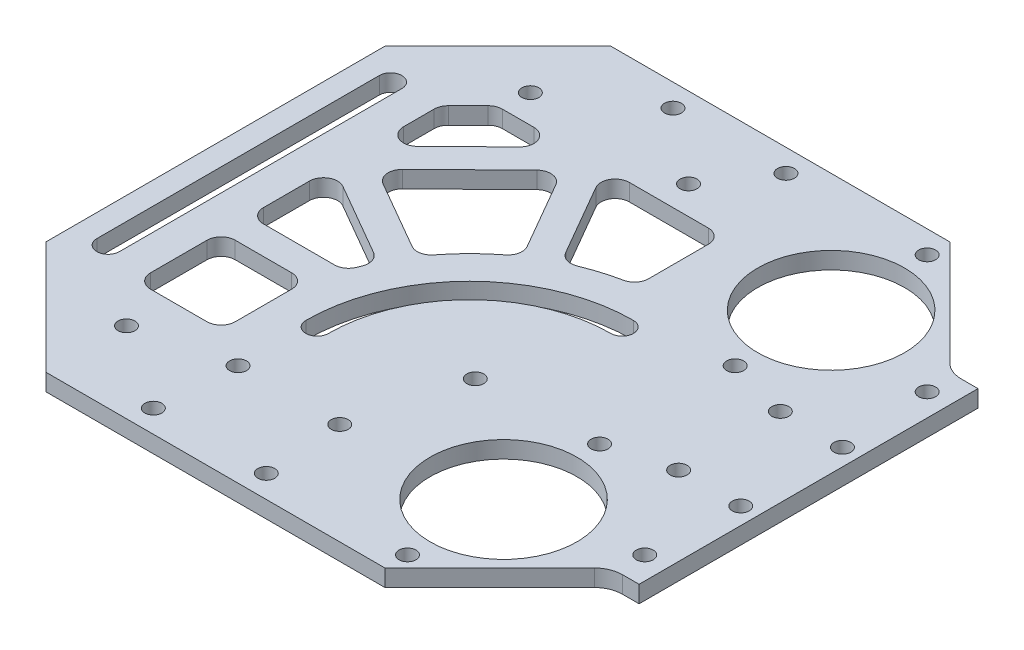
SolidWorks part; units mm, degrees
material "Thornel Mat VMA"
ref_plane "前视基准面" through (0, 0, 0) normal (0, 0, 1) x (1, 0, 0)
ref_plane "上视基准面" through (0, 0, 0) normal (0, 1, 0) x (1, 0, 0)
ref_plane "右视基准面" through (0, 0, 0) normal (1, 0, 0) x (0, 0, -1)
sketch "草图1" plane through (0, 0, 0) normal (0, 1, 0) x (1, 0, 0)
  line L0 (-80, 0) -> (25, 0) construction
  line L1 (22, 9) -> (22, -9) construction
  line L2 (0, 29) -> (0, -29) construction
  line L3 (-60, 50) -> (0, 50)
  line L4 (20, 30) -> (25, 30)
  line L5 (20, -30) -> (25, -30)
  line L6 (0, 50) -> (20, 30)
  line L7 (-60, -50) -> (0, -50)
  line L8 (0, -50) -> (20, -30)
  line L9 (-35, 50) -> (-35, -50) construction
  line L10 (-45, 46) -> (-25, 46) construction
  line L11 (-80, 30) -> (-80, -30)
  line L12 (25, 30) -> (25, -30)
  line L13 (-80, -30) -> (-60, -50)
  line L14 (-44, -32) -> (-26, -32) construction
  line L15 (-60, 50) -> (-80, 30)
  line L16 (11, 9) -> (11, -9) construction
  line L17 (-74, -25) -> (-74, 25) construction
  line L18 (-76, -25) -> (-76, 25)
  line L19 (-72, -25) -> (-72, 25)
  line L20 (-66, -8) -> (-49.1658, -8)
  line L21 (-61, 30.75) -> (-48.273, 30.75)
  line L22 (-66, 25.75) -> (-66, 13.3512)
  line L23 (-66, 25.75) -> (-61, 30.75)
  line L24 (-21, 30.75) -> (-21, 15.5889)
  line L25 (-66, 9.8483) -> (-44.7039, 30.75) construction
  line L26 (-44.7039, 30.75) -> (-33.4545, 11.2653) construction
  line L27 (-66, 9.8483) -> (-46.2653, -1.5455) construction
  line L28 (-61.901, 10.3684) -> (-44.9379, 0.5748)
  line L29 (-61.901, 10.3684) -> (-45.2556, 26.7056)
  line L30 (-45.2556, 26.7056) -> (-35.5748, 9.9379)
  line L31 (-66, 6.9615) -> (-47.4379, -3.7553)
  line L32 (-66, 13.3512) -> (-48.273, 30.75)
  line L33 (-41.8172, 30.75) -> (-31.2447, 12.4379)
  line L34 (-44.1522, 34.7944) -> (-31.2894, 12.5153) construction
  line L35 (-70.099, 9.3281) -> (-44.1522, 34.7944) construction
  line L36 (-41.8172, 30.75) -> (-21, 30.75)
  line L37 (0, -29) -> (0, -46) construction
  line L38 (-70.099, 9.3281) -> (-47.5153, -3.7106) construction
  line L39 (-66, 6.9615) -> (-66, -8)
  line L40 (-45.2556, 26.7056) -> (-35.6195, 10.0153) construction
  line L41 (-61.901, 10.3684) -> (-45.0153, 0.6195) construction
  line L42 (0, -29) -> (-10.9545, 0) construction
  line L43 (-66, -13) -> (-51, -13)
  line L44 (0, 29) -> (0, 46) construction
  line L45 (12.8025, 31.2574) -> (0, 29) construction
  line L46 (-66, -13) -> (-66, -28)
  line L47 (-66, -28) -> (-51, -28)
  line L48 (-51, -13) -> (-51, -28)
  circle A0 centre (-45, 46) radius 1.5
  circle A1 centre (0, 29) radius 13
  circle A2 centre (-25, 46) radius 1.5
  circle A3 centre (-45, -46) radius 1.5
  circle A4 centre (-25, -46) radius 1.5
  arc A5 (-76, -25) -> (-72, -25) centre (-74, -25) ccw
  circle A6 centre (-60, 35.75) radius 1.5
  circle A7 centre (-32, 35.75) radius 1.5
  circle A8 centre (-60, -35.75) radius 1.5
  circle A9 centre (-26, -32) radius 1.5
  circle A10 centre (-44, -32) radius 1.5
  circle A11 centre (11, -9) radius 1.5
  circle A12 centre (11, 9) radius 1.5
  circle A13 centre (-21, -13) radius 1.5
  circle A14 centre (0, -46) radius 1.5
  circle A15 centre (0, 46) radius 1.5
  arc A16 (-72, 25) -> (-76, 25) centre (-74, 25) ccw
  arc A17 (-21, 15.5889) -> (-31.2447, 12.4379) centre (-15.9545, -19.0455) ccw
  arc A18 (-47.4379, -3.7553) -> (-49.1658, -8) centre (-15.9545, -19.0455) ccw
  arc A19 (-35.5748, 9.9379) -> (-44.9379, 0.5748) centre (-15.9545, -19.0455) ccw
  arc A20 (-35, -19.0455) -> (-15.9545, 0) centre (-15.9545, -19.0455) cw construction
  arc A21 (-42.9545, -19.0455) -> (-15.9545, 7.9545) centre (-15.9545, -19.0455) cw construction
  circle A22 centre (0, -29) radius 13
  circle A23 centre (22, 9) radius 1.5
  circle A24 centre (22, -9) radius 1.5
  arc A25 (-15.9545, 9.9545) -> (-44.9545, -19.0455) centre (-15.9545, -19.0455) ccw
  arc A26 (-15.9545, 5.9545) -> (-40.9545, -19.0455) centre (-15.9545, -19.0455) ccw
  arc A27 (-15.9545, 5.9545) -> (-15.9545, 9.9545) centre (-15.9545, 7.9545) ccw
  arc A28 (-44.9545, -19.0455) -> (-40.9545, -19.0455) centre (-42.9545, -19.0455) ccw
  circle A29 centre (21, 25) radius 1.5
  circle A30 centre (21, -25) radius 1.5
  circle A38 centre (0, -12) radius 1.5
  circle A39 centre (0, 12) radius 1.5
  point P2 (0, 0)
  point P14 (-35, 46)
  point P45 (-35, -32)
  point P49 (-74, 0)
  point P50 (11, 0)
  point P61 (-21, 23.1694)
  point P100 (-35.0463, 0.0463)
  dimension "D9" = 5
  dimension "D10" = 45
  dimension "D11" = 28
  dimension "D13" = 20
  dimension "D14" = 3
  dimension "D22" = 20
  dimension "D23" = 3
  dimension "D30" = 80
  dimension "D32" = 3
  dimension "D20" = 3
  dimension "D36" = 3
  dimension "D5" = 3
  dimension "D7" = 100
  dimension "D8" = 35
  dimension "D37" = 14
  dimension "D38" = 2
  dimension "D41" = 5
  dimension "D45" = 8
  dimension "D18" = 18
  dimension "D29" = 26
  dimension "D48" = 2.5
  dimension "D49" = 2.5
  dimension "D53" = 5
  dimension "D57" = 2
  dimension "D62" = 0
  dimension "D39" = 50
  dimension "D40" = 8
  dimension "D58" = 3
  dimension "D59" = 50
  dimension "D16" = 71.5
  dimension "D17" = 20
  dimension "D55" = 5
  dimension "D35" = 13
  dimension "D47" = 5
  dimension "D25" = 18
  dimension "D33" = 3
  dimension "D34" = 3
  dimension "D44" = 35
  dimension "D56" = 27
  dimension "D60" = 4
  dimension "D1" = 60
  dimension "D12" = 4
  dimension "D15" = 58
  dimension "D19" = 80
  dimension "D21" = 45
  dimension "D24" = 18
  dimension "D26" = 18
  dimension "D27" = 14
  dimension "D28" = 22
  dimension "D31" = 6
  dimension "D42" = 14
  dimension "D43" = 17
  dimension "D46" = 5
  dimension "D50" = 30
  dimension "D51" = 30
  dimension "D52" = 15
  dimension "D54" = 31
  dimension "D63" = 12
extrude "凸台-拉伸1" add sketch "草图1" along normal blind 3
fillet "圆角1" radius 2.5 20 edges at (-51, 1.5, 28) (-51, 1.5, 13) (-66, 1.5, 13) (-66, 1.5, 28) (-21, 1.5, -30.75) (-41.8172, 1.5, -30.75) (-31.2447, 1.5, -12.4379) (-21, 1.5, -15.5889) (-49.1658, 1.5, 8) (-47.4379, 1.5, 3.7553) (-66, 1.5, -6.9615) (-66, 1.5, 8) (-66, 1.5, -13.3512) (-61, 1.5, -30.75) (-44.9379, 1.5, -0.5748) (-35.5748, 1.5, -9.9379) (-45.2556, 1.5, -26.7056) (-61.901, 1.5, -10.3684) (-66, 1.5, -25.75) (-48.273, 1.5, -30.75)
fillet "圆角2" radius 5 2 edges at (20, 1.5, -30) (20, 1.5, 30)
